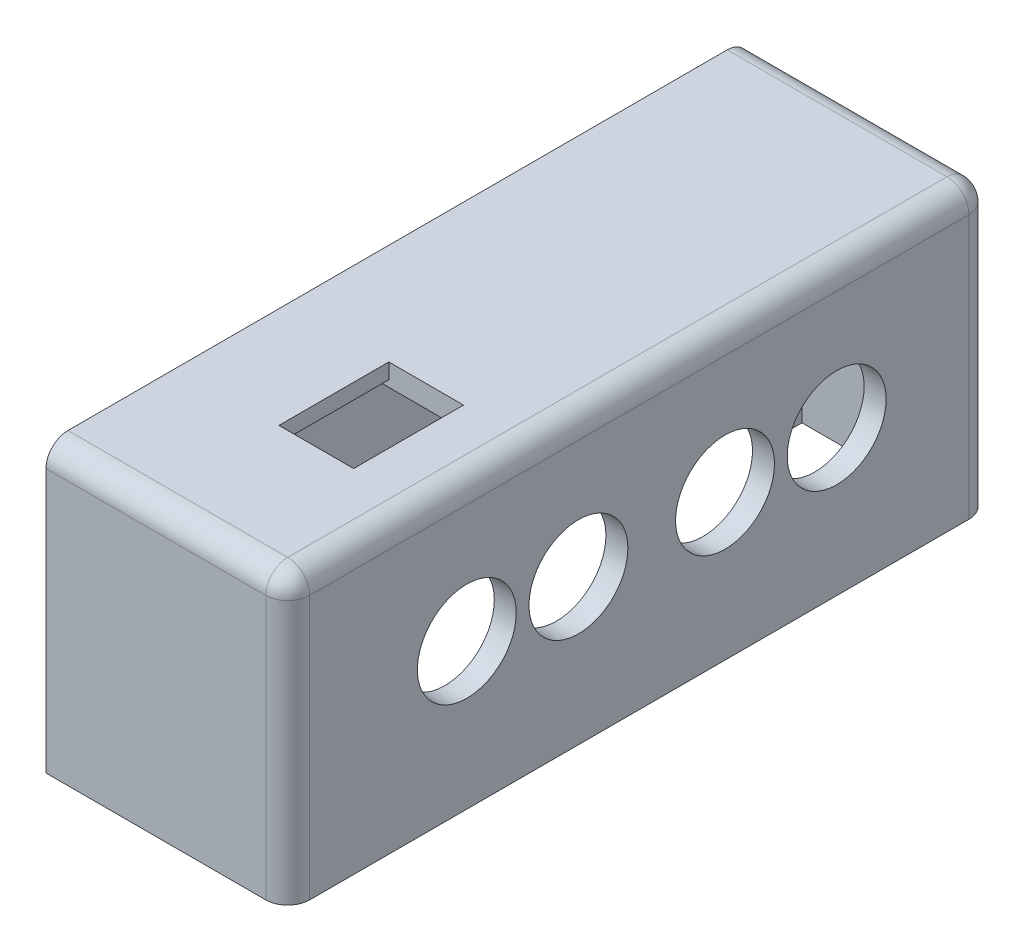
SolidWorks part; units mm, degrees
ref_plane "Спереди" through (0, 0, 0) normal (0, 0, 1) x (1, 0, 0)
ref_plane "Сверху" through (0, 0, 0) normal (0, 1, 0) x (1, 0, 0)
ref_plane "Справа" through (0, 0, 0) normal (1, 0, 0) x (0, 0, -1)
sketch "Эскиз1" plane through (0, 0, 0) normal (1, 0, 0) x (0, 0, -1)
  line L1 (-80, -32.5) -> (80, -32.5)
  line L2 (-80, -32.5) -> (-80, 32.5)
  line L3 (-80, 32.5) -> (80, 32.5)
  line L4 (80, -32.5) -> (80, 32.5)
  line L5 (-80, -32.5) -> (80, 32.5) construction
  line L6 (-80, 32.5) -> (80, -32.5) construction
  point P0 (0, 0)
  dimension "D1" = 65
  dimension "D2" = 160
extrude "Бобышка-Вытянуть1" add sketch "Эскиз1" along normal blind 55 contours L3 L4 L1 L2
sketch "Эскиз2" plane through (0, -32.5, 0) normal (0, -1, 0) x (1, 0, 0)
  line L0 (5, -71) -> (10, -71)
  line L5 (50, -71) -> (44, -71)
  line L7 (10, 71) -> (5, 71)
  line L14 (10, 71) -> (13, 71)
  line L15 (13, 71) -> (13, 75)
  line L16 (13, 75) -> (14, 75)
  line L17 (14, 75) -> (14, 71)
  line L18 (14, 71) -> (17, 71)
  line L19 (17, 71) -> (17, 75)
  line L20 (17, 75) -> (37, 75)
  line L21 (37, 75) -> (37, 71)
  line L22 (37, 71) -> (40, 71)
  line L23 (40, 71) -> (40, 75)
  line L24 (40, 75) -> (41, 75)
  line L25 (41, 75) -> (41, 71)
  line L26 (41, 71) -> (44, 71)
  line L29 (5, 71) -> (5, -71)
  line L32 (10, -71) -> (13, -71)
  line L33 (13, -71) -> (13, -75)
  line L34 (13, -75) -> (14, -75)
  line L35 (14, -75) -> (14, -71)
  line L36 (14, -71) -> (17, -71)
  line L37 (17, -71) -> (17, -75)
  line L38 (17, -75) -> (37, -75)
  line L39 (37, -75) -> (37, -71)
  line L40 (37, -71) -> (40, -71)
  line L41 (40, -71) -> (40, -75)
  line L42 (40, -75) -> (41, -75)
  line L43 (41, -75) -> (41, -71)
  line L44 (41, -71) -> (44, -71)
  line L47 (50, -71) -> (50, 71)
  line L48 (50, 71) -> (44, 71)
  line L49 (0, 80) -> (0, -80) construction
  line L50 (55, 80) -> (55, -80) construction
  line L51 (55, 80) -> (0, 80) construction
  line L52 (55, -80) -> (0, -80) construction
  dimension "D2" = 5
  dimension "D3" = 5
  dimension "D4" = 5
  dimension "D5" = 6
  dimension "D6" = 3
  dimension "D7" = 3
  dimension "D8" = 3
  dimension "D9" = 3
  dimension "D10" = 1
  dimension "D11" = 1
  dimension "D12" = 6
  dimension "D13" = 20
  dimension "D14" = 5
  dimension "D15" = 5
  dimension "D16" = 9
  dimension "D17" = 9
  dimension "D18" = 5
extrude "Вырез-Вытянуть3" cut sketch "Эскиз2" against normal blind 60 contours L29 L0 L32 L33 L34 L35 L36 L37 L38 L39 L40 L41 L42 L43 L44 L5 L47 L48 L26 L25 L24 L23 L22 L21 L20 L19 L18 L17 L16 L15 L14 L7
sketch "Эскиз6" plane through (0, 32.5, 0) normal (0, 1, 0) x (1, 0, 0)
  line L0 (55, -80) -> (0, -80) construction
  line L1 (23, -25) -> (40, -25)
  line L2 (23, -25) -> (23, -50)
  line L3 (23, -50) -> (40, -50)
  line L4 (40, -25) -> (40, -50)
  line L5 (55, -80) -> (55, 80) construction
  dimension "D1" = 17
  dimension "D2" = 25
  dimension "D3" = 30
  dimension "D4" = 15
extrude "Вырез-Вытянуть4" cut sketch "Эскиз6" against normal blind 60
sketch "Эскиз7" plane through (0, 27.5, 0) normal (0, -1, 0) x (1, 0, 0)
  line L0 (23, 25) -> (23, 50) construction
  line L1 (18, 50) -> (45, 50)
  line L2 (18, 50) -> (18, 25)
  line L3 (18, 25) -> (45, 25)
  line L4 (45, 50) -> (45, 25)
  line L5 (40, 50) -> (40, 25) construction
  line L6 (23, 50) -> (40, 50) construction
  line L7 (40, 25) -> (23, 25) construction
  dimension "D1" = 5
  dimension "D2" = 5
extrude "Вырез-Вытянуть5" cut sketch "Эскиз7" against normal blind 1.5
sketch "Эскиз9" plane through (55, 0, 0) normal (1, 0, 0) x (0, 0, -1)
  line L0 (-80, 32.5) -> (80, 32.5) construction
  line L1 (-1036.75, 0.6) -> (48963.25, 0.6) construction
  line L2 (-80, -32.5) -> (-80, 32.5) construction
  line L4 (80, -32.5) -> (80, 32.5) construction
  circle A0 centre (-39.25, 0.6) radius 11.25
  circle A4 centre (19.503, 0.6) radius 11.25
  circle A5 centre (44.903, 0.6) radius 11.25
  circle A7 centre (-13.85, 0.6) radius 11.25
  point P6 (0, 0)
  point P7 (0, 0)
  point P8 (0, 0)
  point P15 (0, 0)
  point P16 (0, 0)
  point P17 (0, 0)
  point P18 (0, 0)
  point P21 (0, 0)
  dimension "D1" = 31.9
  dimension "D2" = 22.5
  dimension "D7" = 22.5
  dimension "D8" = 22.5
  dimension "D9" = 22.5
  dimension "D10" = 35.097
  dimension "D3" = 25.4
  dimension "D4" = 33.353
  dimension "D5" = 25.4
  dimension "D6" = 40.75
extrude "Вырез-Вытянуть6" cut sketch "Эскиз9" against normal blind 10
fillet "Скругление3" radius 5 5 edges at (55, 0, 80) (27.5, 32.5, 80) (55, 32.5, 0) (27.5, 32.5, -80) (55, 0, -80)
sketch "Эскиз10" plane through (0, -32.5, 0) normal (0, -1, 0) x (1, 0, 0)
  line L0 (50, 80) -> (0, 80) construction
  line L1 (51.5588, 72.3) -> (53.1177, 75)
  line L2 (53.1177, 75) -> (51.5588, 77.7)
  line L3 (51.5588, 77.7) -> (48.4412, 77.7)
  line L4 (48.4412, 77.7) -> (46.8823, 75)
  line L5 (46.8823, 75) -> (48.4412, 72.3)
  line L6 (48.4412, 72.3) -> (51.5588, 72.3)
  line L8 (55, 75) -> (55, -75) construction
  line L28 (0, 80) -> (0, -80) construction
  line L29 (6.5588, 72.3) -> (8.1177, 75)
  line L30 (8.1177, 75) -> (6.5588, 77.7)
  line L31 (6.5588, 77.7) -> (3.4412, 77.7)
  line L32 (3.4412, 77.7) -> (1.8823, 75)
  line L33 (1.8823, 75) -> (3.4412, 72.3)
  line L34 (3.4412, 72.3) -> (6.5588, 72.3)
  line L35 (8.1177, -75) -> (6.5588, -72.3)
  line L36 (6.5588, -72.3) -> (3.4412, -72.3)
  line L37 (3.4412, -72.3) -> (1.8823, -75)
  line L38 (1.8823, -75) -> (3.4412, -77.7)
  line L39 (3.4412, -77.7) -> (6.5588, -77.7)
  line L40 (6.5588, -77.7) -> (8.1177, -75)
  line L41 (51.5588, -77.7) -> (53.1177, -75)
  line L42 (53.1177, -75) -> (51.5588, -72.3)
  line L43 (51.5588, -72.3) -> (48.4412, -72.3)
  line L44 (48.4412, -72.3) -> (46.8823, -75)
  line L45 (46.8823, -75) -> (48.4412, -77.7)
  line L46 (48.4412, -77.7) -> (51.5588, -77.7)
  line L47 (50, -80) -> (0, -80) construction
  circle A0 centre (50, 75) radius 2.7 construction
  circle A1 centre (5, 75) radius 2.7 construction
  circle A2 centre (5, -75) radius 2.7 construction
  circle A3 centre (50, -75) radius 2.7 construction
  point P43 (0, 0)
  dimension "D1" = 5.4
  dimension "D2" = 5
  dimension "D3" = 5
  dimension "D4" = 5
  dimension "D5" = 5
  dimension "D6" = 5.4
  dimension "D7" = 5
  dimension "D8" = 5
  dimension "D9" = 5.4
  dimension "D10" = 5
  dimension "D11" = 5
  dimension "D12" = 5.4
extrude "Вырез-Вытянуть7" cut sketch "Эскиз10" against normal blind 2.34
sketch "Эскиз12" plane through (0, -32.5, 0) normal (0, -1, 0) x (1, 0, 0)
  line L0 (55, 75) -> (55, -75) construction
  line L1 (50, 80) -> (0, 80) construction
  line L2 (0, 80) -> (0, -80) construction
  line L3 (50, -80) -> (0, -80) construction
  circle A0 centre (50, 75) radius 1.5
  circle A1 centre (50, -75) radius 1.5
  circle A2 centre (5, -75) radius 1.5
  circle A3 centre (5, 75) radius 1.5
  point P12 (0, 0)
  point P19 (14.5672, -51.1425)
  dimension "D1" = 5
  dimension "D3" = 3
  dimension "D4" = 3
  dimension "D9" = 3
  dimension "D10" = 3
  dimension "D2" = 5
  dimension "D5" = 5
  dimension "D6" = 5
  dimension "D7" = 5
  dimension "D8" = 5
  dimension "D11" = 5
  dimension "D12" = 5
extrude "Вырез-Вытянуть8" cut sketch "Эскиз12" against normal blind 4
